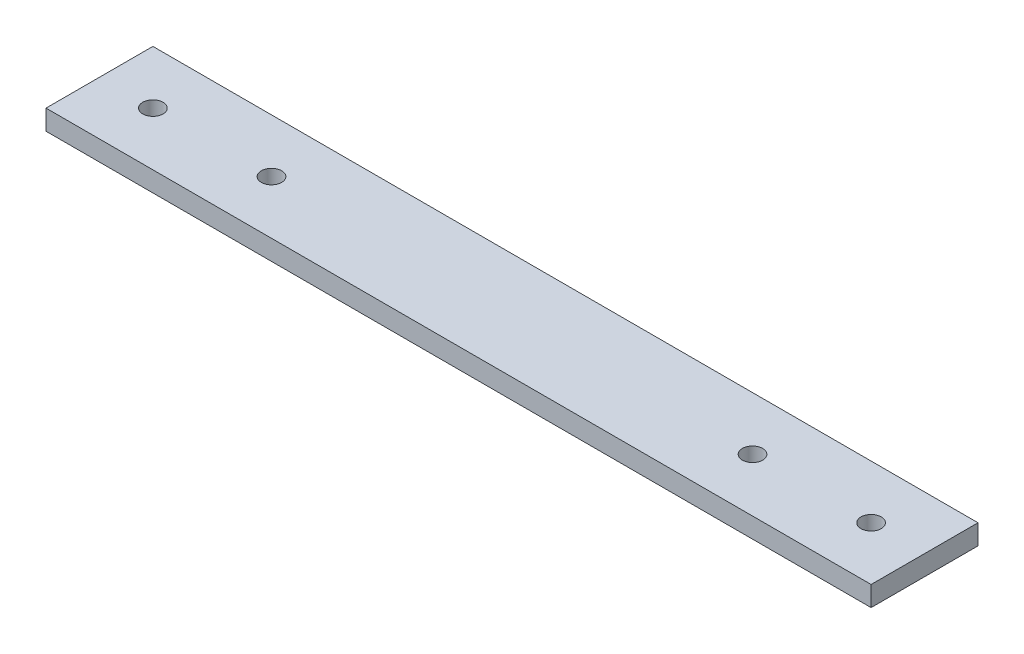
SolidWorks part; units mm, degrees
material "6061-T6 (SS)"
ref_plane "Front Plane" through (0, 0, 0) normal (0, 0, 1) x (1, 0, 0)
ref_plane "Top Plane" through (0, 0, 0) normal (0, 1, 0) x (1, 0, 0)
ref_plane "Right Plane" through (0, 0, 0) normal (1, 0, 0) x (0, 0, -1)
sketch "Sketch1" plane through (0, 0, 0) normal (0, 1, 0) x (1, 0, 0)
  line L1 (98.0313, -12.7) -> (-98.0313, -12.7)
  line L2 (98.0313, -12.7) -> (98.0313, 12.7)
  line L3 (98.0313, 12.7) -> (-98.0313, 12.7)
  line L4 (-98.0313, -12.7) -> (-98.0313, 12.7)
  line L5 (98.0313, -12.7) -> (-98.0313, 12.7) construction
  line L6 (98.0313, 12.7) -> (-98.0313, -12.7) construction
  point P0 (0, 0)
  dimension "D1" = 196.0626
  dimension "D2" = 25.4
extrude "Boss-Extrude1" add sketch "Sketch1" along normal blind 4.7625
sketch "Sketch2" plane through (0, 4.7625, 0) normal (0, 1, 0) x (1, 0, 0)
  line L0 (98.0313, -12.7) -> (98.0313, 12.7) construction
  line L1 (-98.0313, 12.7) -> (-98.0313, -12.7) construction
  circle A0 centre (-57.15, 0) radius 2.413
  circle A1 centre (57.15, 0) radius 2.413
  circle A2 centre (-85.3313, 0) radius 2.413
  circle A3 centre (85.3313, 0) radius 2.413
  dimension "D1" = 4.826
  dimension "D2" = 4.826
  dimension "D5" = 4.826
  dimension "D6" = 4.826
  dimension "D3" = 40.8813
  dimension "D4" = 40.8813
  dimension "D7" = 12.7
  dimension "D8" = 12.7
extrude "Cut-Extrude1" cut sketch "Sketch2" against normal through all
